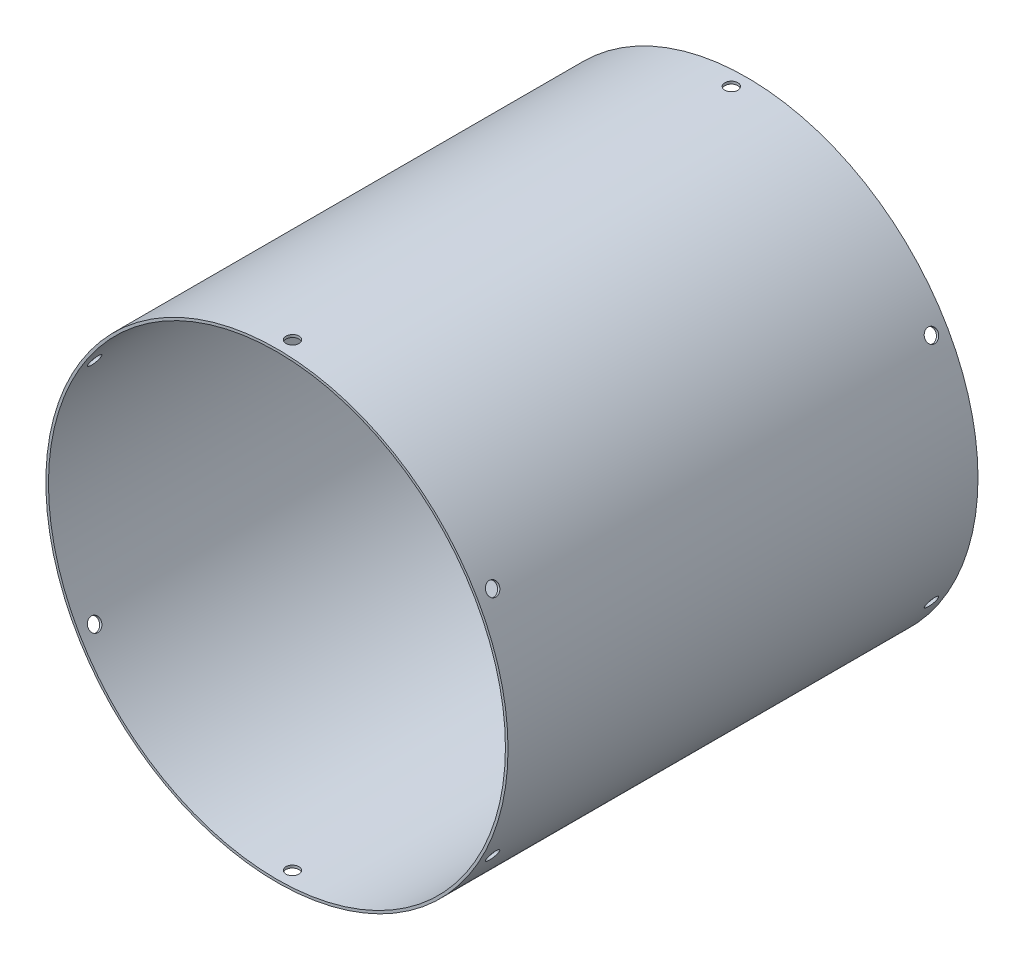
SolidWorks part; units mm, degrees
material "AISI Type 316L stainless steel"
ref_plane "Front Plane" through (0, 0, 0) normal (0, 0, 1) x (1, 0, 0)
ref_plane "Top Plane" through (0, 0, 0) normal (0, 1, 0) x (1, 0, 0)
ref_plane "Right Plane" through (0, 0, 0) normal (1, 0, 0) x (0, 0, -1)
sketch "Sketch1" plane through (0, 0, 0) normal (0, 0, 1) x (1, 0, 0)
  circle A0 centre (0, 0) radius 44
  circle A1 centre (0, 0) radius 44.5
  dimension "D1" = 0.5
  dimension "D2" = 88
extrude "Boss-Extrude1" add sketch "Sketch1" along normal blind 90.5
sketch "Sketch2" plane through (0, 0, 0) normal (0, 1, 0) x (1, 0, 0)
  line L0 (0, 0) -> (0, -94.5649) construction
  line L1 (44.5, 0) -> (-44.5, 0) construction
  line L2 (-44.5, -90.5) -> (44.5, -90.5) construction
  circle A0 centre (0, -3) radius 1.25
  circle A1 centre (0, -87.5) radius 1.25
  dimension "D1" = 2.5
  dimension "D2" = 3
  dimension "D3" = 3
extrude "Cut-Extrude1" cut sketch "Sketch2" against normal through all
ref_axis "Axis1" through (0, 0, 90.5) along (0, 0, -1)
pattern_circular "CirPattern1" count 6 over 360 about axis through (0, 0, 90.5) along (0, 0, -1) of "Cut-Extrude1"
ref_plane "Plane1" through (0, 0, 0) normal (0.9576, -0.2882, 0) x (0, 0, -1)
sketch "Sketch3" plane through (0, 0, 0) normal (0.9576, -0.2882, 0) x (0, 0, -1)
  line L0 (-90.5, 0) -> (0, 0) construction
  line L1 (-90.5, 44.5) -> (-90.5, -44.5) construction
  circle A0 centre (-42, 0) radius 3.5
  dimension "D1" = 7
  dimension "D2" = 48.5
extrude "Cut-Extrude2" cut sketch "Sketch3" against normal through all
pattern_circular "CirPattern2" count 2 every 120 about axis through (0, 0, 90.5) along (0, 0, -1) of "Cut-Extrude2"
